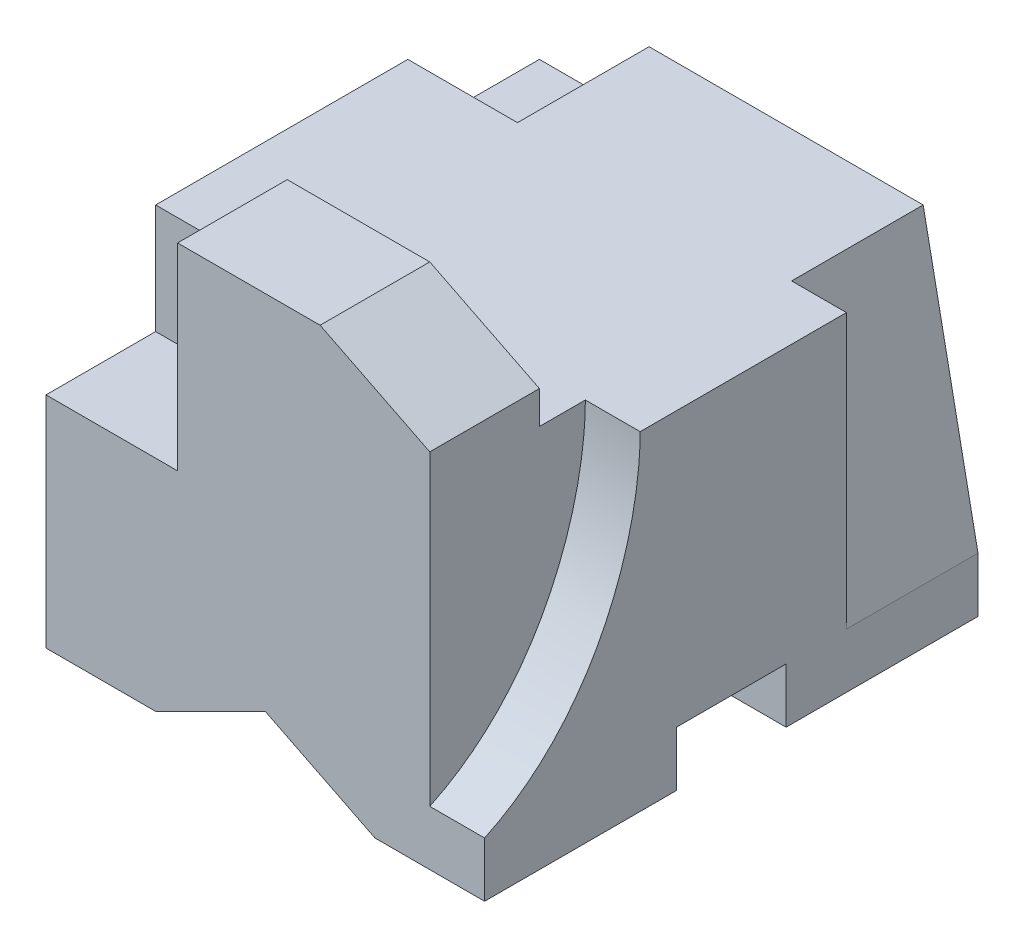
SolidWorks part; units mm, degrees
ref_plane "Спереди" through (0, 0, 0) normal (0, 0, 1) x (1, 0, 0)
ref_plane "Сверху" through (0, 0, 0) normal (0, 1, 0) x (1, 0, 0)
ref_plane "Справа" through (0, 0, 0) normal (1, 0, 0) x (0, 0, -1)
sketch "Эскиз1" plane through (0, 0, 0) normal (1, 0, 0) x (0, 0, -1)
  line L1 (-22.5, -15) -> (22.5, -15)
  line L2 (-22.5, -15) -> (-22.5, 15)
  line L3 (-22.5, 15) -> (22.5, 15)
  line L4 (22.5, -15) -> (22.5, 15)
  line L5 (-22.5, -15) -> (22.5, 15) construction
  line L6 (-22.5, 15) -> (22.5, -15) construction
  point P0 (0, 0)
  dimension "D1" = 45
  dimension "D2" = 30
extrude "Бобышка-Вытянуть1" add sketch "Эскиз1" along normal blind 40
sketch "Эскиз2" plane through (40, 0, 0) normal (1, 0, 0) x (0, 0, -1)
  line L0 (0, 15) -> (0, -15) construction
  line L1 (22.5, 15) -> (-22.5, 15) construction
  line L2 (-22.5, -15) -> (22.5, -15) construction
  line L4 (-5, -15) -> (5, -15)
  line L5 (-5, -15) -> (-5, -13)
  line L6 (-5, -13) -> (5, -13)
  line L7 (5, -15) -> (5, -13)
  line L8 (-5, -15) -> (5, -13) construction
  line L9 (-5, -13) -> (5, -15) construction
  line L10 (-5, -13) -> (5, -13)
  line L11 (-5, -13) -> (-5, -10)
  line L12 (-5, -10) -> (5, -10)
  line L13 (5, -13) -> (5, -10)
  line L14 (-5, -13) -> (5, -10) construction
  line L15 (-5, -10) -> (5, -13) construction
  point P6 (0, -14)
  point P11 (0, -11.5)
  line M4 (-22.5, -15) -> (22.5, -15)
  dimension "D1" = 2
  dimension "D2" = 10
  dimension "D3" = 10
  dimension "D4" = 3
extrude "Вырез-Вытянуть1" cut sketch "Эскиз2" against normal through all contours L6 L13 L12 L11 | L7 L6 L5 M4
sketch "Эскиз3" plane through (40, 0, 0) normal (1, 0, 0) x (0, 0, -1)
  line L0 (-22.5, 15) -> (-22.5, -10)
  line L1 (-22.5, 15) -> (-22.5, -15) construction
  line L2 (-22.5, 15) -> (-8.3099, 15)
  line L3 (22.5, 15) -> (-22.5, 15) construction
  line L4 (-5, -10) -> (5, -10) construction
  spline S0 degree 3 poles (-8.3099, 15) (-8.3099, 6.5812) (-12.4623, -5.2924) (-22.5, -10) knots 0 0 0 0 1 1 1 1
extrude "Вырез-Вытянуть2" cut sketch "Эскиз3" against normal blind 5
sketch "Эскиз4" plane through (0, 0, -22.5) normal (0, 0, -1) x (-1, 0, 0)
  line L0 (-40, 15) -> (-35, 15)
  line L1 (-40, 15) -> (0, 15) construction
  line L2 (-35, 15) -> (-40, -10)
  line L3 (-40, -15) -> (-40, 15) construction
  line L4 (-40, -10) -> (-40, 15)
  line L5 (-35, 15) -> (-40, 15) construction
  line L6 (-35, 15) -> (-35, -10) construction
extrude "Вырез-Вытянуть3" cut sketch "Эскиз4" against normal blind 12
sketch "Эскиз5" plane through (0, 0, 22.5) normal (0, 0, 1) x (1, 0, 0)
  line L0 (20, -15) -> (20, 15) construction
  line L1 (40, -15) -> (0, -15) construction
  line L2 (35, 15) -> (0, 15) construction
  line L3 (20, -10) -> (30, -15)
  line L4 (30, -15) -> (10, -15)
  line L5 (0, -10) -> (40, -10) construction
  line L6 (20, -10) -> (10, -15)
  dimension "D1" = 10
extrude "Вырез-Вытянуть4" cut sketch "Эскиз5" against normal through all
sketch "Эскиз6" plane through (0, 0, 22.5) normal (0, 0, 1) x (1, 0, 0)
  line L0 (35, 15) -> (40, 15) construction
  line L1 (0, 15) -> (5, 15)
  line L2 (0, 15) -> (0, 5)
  line L3 (0, 5) -> (5, 5)
  line L4 (5, 15) -> (5, 5)
  dimension "D1" = 10
extrude "Вырез-Вытянуть5" cut sketch "Эскиз6" against normal up to vertex (14.1901 mm away) up to point (40, 15, 8.3099)
sketch "Эскиз7" plane through (0, 0, 22.5) normal (0, 0, 1) x (1, 0, 0)
  line L0 (20, 15) -> (20, -10) construction
  line L1 (35, 15) -> (5, 15) construction
  line L2 (35, 15) -> (35, 18)
  line L3 (35, 18) -> (25, 23)
  line L4 (25, 23) -> (15, 23)
  line L5 (5, 15) -> (5, 18)
  line L6 (5, 18) -> (15, 23)
  line L7 (5, 15) -> (35, 15)
  point P11 (20, 23)
  dimension "D1" = 3
  dimension "D2" = 8
  dimension "D3" = 5
extrude "Бобышка-Вытянуть2" add sketch "Эскиз7" against normal blind 10
sketch "Эскиз8" plane through (0, 0, 0) normal (-1, 0, 0) x (0, 0, 1)
  line L1 (-10.5, 9) -> (-10.5, 15)
  line L2 (-22.5, 15) -> (8.3099, 15) construction
  line L3 (-10.5, 15) -> (-22.5, 15)
  line L4 (-10.5, 15) -> (-22.5, 15) construction
  line L5 (-22.5, 15) -> (-22.5, 9)
  line L6 (-22.5, -15) -> (-22.5, 15) construction
  line L7 (-22.5, 9) -> (-10.5, 9)
  dimension "D1" = 6
extrude "Вырез-Вытянуть6" cut sketch "Эскиз8" against normal blind 10
sketch "Эскиз9" plane through (0, 0, 22.5) normal (0, 0, 1) x (1, 0, 0)
  line L1 (0, 5) -> (12, 5)
  line L2 (0, 5) -> (0, 23)
  line L3 (0, 23) -> (12, 23)
  line L4 (12, 5) -> (12, 23)
  dimension "D1" = 12
extrude "Вырез-Вытянуть7" cut sketch "Эскиз9" against normal up to surface (10 mm away) up to face at (17.5, 18.6667, 12.5)
sketch "Эскиз10" plane through (0, 0, 8.3099) normal (0, 0, 1) x (1, 0, 0)
  line L4 (0, 15) -> (0, 5)
  line L5 (0, 5) -> (5, 5)
  line L6 (5, 5) -> (5, 15)
  line L7 (5, 15) -> (0, 15)
  line L8 (0, 15) -> (0, 5)
  line L9 (0, 5) -> (5, 5)
  line L10 (5, 5) -> (5, 15)
  line L11 (5, 15) -> (0, 15)
  dimension "D1" = 0
extrude "Бобышка-Вытянуть3" add sketch "Эскиз10" along normal up to surface (4.1901 mm away)
sketch "Эскиз11" plane through (0, 0, 22.5) normal (0, 0, 1) x (1, 0, 0)
  line L0 (15, 23) -> (12, 21.5)
  line L1 (12, 21.5) -> (12, 23)
  line L2 (12, 23) -> (15, 23)
extrude "Бобышка-Вытянуть4" add sketch "Эскиз11" against normal up to surface (10 mm away) up to face at (20.4167, 19, 12.5)
